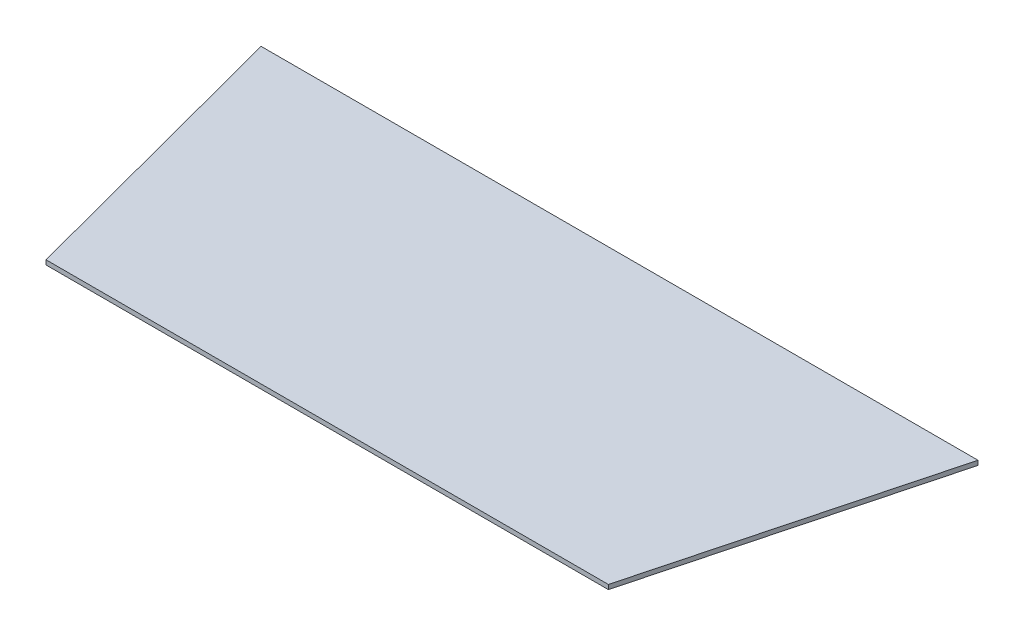
SolidWorks part; units mm, degrees
ref_plane "Front Plane" through (0, 0, 0) normal (0, 0, 1) x (1, 0, 0)
ref_plane "Top Plane" through (0, 0, 0) normal (0, 1, 0) x (1, 0, 0)
ref_plane "Right Plane" through (0, 0, 0) normal (1, 0, 0) x (0, 0, -1)
sketch "Sketch1" plane through (0, 0, 0) normal (0, 1, 0) x (1, 0, 0)
  line L0 (66.0803, 649.8963) -> (237.7903, 0)
  line L1 (237.7903, 0) -> (1487.7903, 0)
  line L3 (66.0803, 649.8963) -> (1659.5003, 649.8963)
  line L5 (1659.5003, 649.8963) -> (1487.7903, 0)
  dimension "D1" = 649.8963
  dimension "D2" = 1250
  dimension "D3" = 104.8
  dimension "D4" = 104.8
  dimension "Length" = 1593.42
extrude "Extrude1" add sketch "Sketch1" along normal blind 10
